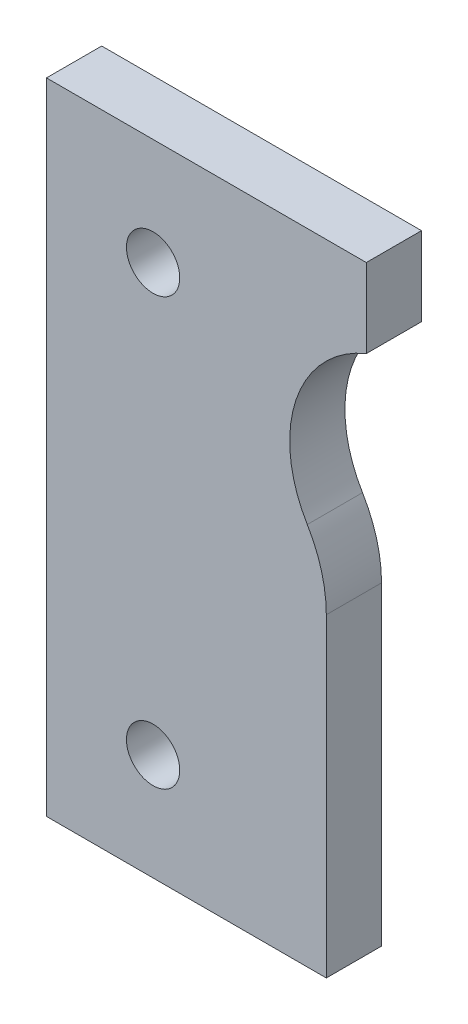
SolidWorks part; units mm, degrees
material "6061 Alloy"
ref_plane "X-Y Datum" through (0, 0, 0) normal (0, 0, 1) x (1, 0, 0)
ref_plane "X-Z Datum" through (0, 0, 0) normal (0, 1, 0) x (1, 0, 0)
ref_plane "Y-Z Datum" through (0, 0, 0) normal (1, 0, 0) x (0, 0, -1)
sketch "Sketch2" plane through (0, 0, 0) normal (0, 0, 1) x (1, 0, 0)
  line L6 (-16.6687, -15.7343) -> (-16.6687, -39.6173)
  line L10 (-16.6687, -39.6173) -> (-16.6687, -49.3893)
  line L14 (-16.6687, -53.2128) -> (-16.6687, -49.3893)
  line L16 (-50.0062, 22.9872) -> (-50.0062, -53.2128)
  line L17 (-50.0062, -53.2128) -> (-16.6687, -53.2128)
  line L18 (-11.9062, 22.9872) -> (-50.0062, 22.9872)
  line L29 (-11.9062, 22.9872) -> (-11.9062, 13.5892)
  arc A5 (-11.9062, 13.5892) -> (-18.9352, -7.5598) centre (-6.35, 0) ccw
  arc A7 (-16.6687, -15.7343) -> (-18.9352, -7.5598) centre (-32.5437, -15.7343) ccw
  dimension "D1" = 76.2
  dimension "D2" = 38.1
  dimension "D3" = 9.398
extrude "Boss-Extrude1" add sketch "Sketch2" along normal blind 6.5786
sketch "Sketch3" plane through (0, 0, 6.5786) normal (0, 0, 1) x (1, 0, 0)
  line L0 (-50.0062, 22.9872) -> (-50.0062, -53.2128) construction
  line L1 (-11.9062, 22.9872) -> (-50.0062, 22.9872) construction
  line L2 (-50.0062, -53.2128) -> (-16.6687, -53.2128) construction
  point P0 (-37.3062, 10.2872)
  point P1 (-37.3062, -40.5128)
  dimension "D1" = 12.7
  dimension "D2" = 12.7
  dimension "D3" = 12.7
  dimension "D4" = 12.7
hole_wizard "#97 (0.25) Diameter Hole1" positions "3DSketch1" profile "Sketch4" hole size "#97" standard "ANSI Inch" end condition through all
sketch3d "3DSketch1"
  point P0 (-37.3062, 10.2872, 6.5786)
  point P3 (-37.3062, -40.5128, 6.5786)
sketch "Sketch4" plane through (-37.3062, 10.2872, 6.5786) normal (1, 0, 0) x (0, -1, 0)
  line L0 (0, 0) -> (0, 6.5786)
  line L1 (0, 6.5786) -> (3.175, 6.5786)
  line L2 (3.175, 6.5786) -> (3.175, 0)
  line L5 (3.175, 0) -> (0, 0)
  line L11 (0, -6.35) -> (0, 107.95) construction
  dimension "Thru Hole Dia." = 6.35
  dimension "Thru Hole Depth" = 6.5786
